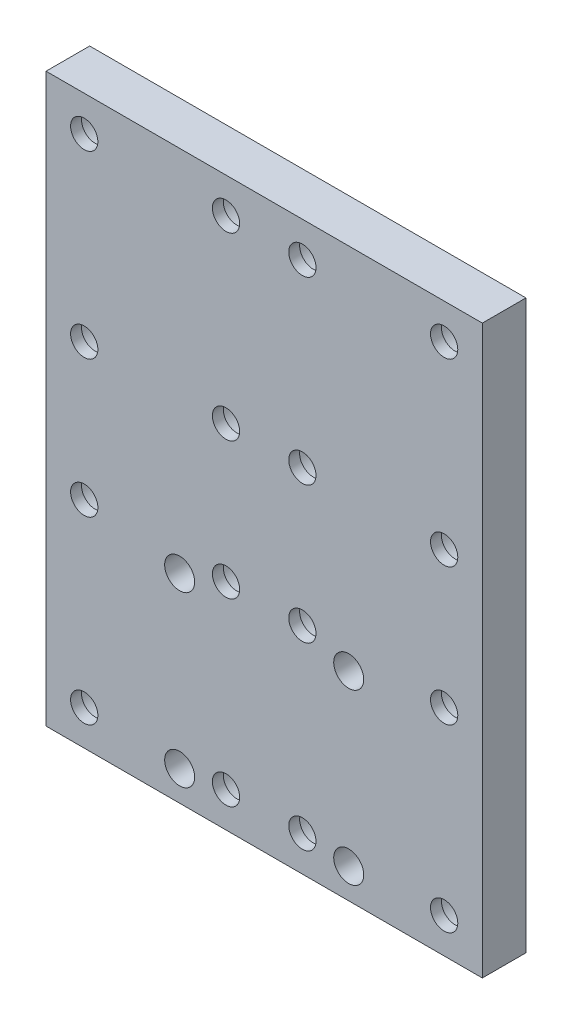
SolidWorks part; units mm, degrees
ref_plane "Ön Düzlem" through (0, 0, 0) normal (0, 0, 1) x (1, 0, 0)
ref_plane "Üst Düzlem" through (0, 0, 0) normal (0, 1, 0) x (1, 0, 0)
ref_plane "Sağ Düzlem" through (0, 0, 0) normal (1, 0, 0) x (0, 0, -1)
sketch "Sketch1" plane through (0, 0, 0) normal (0, 0, 1) x (1, 0, 0)
  line L1 (-40, -52) -> (40, -52)
  line L2 (-40, -52) -> (-40, 52)
  line L3 (-40, 52) -> (40, 52)
  line L4 (40, -52) -> (40, 52)
  line L5 (-40, -52) -> (40, 52) construction
  line L6 (-40, 52) -> (40, -52) construction
  point P0 (0, 0)
  dimension "D1" = 80
  dimension "D2" = 104
extrude "Boss-Extrude1" add sketch "Sketch1" along normal blind 8
sketch "Sketch2" plane through (0, 0, 8) normal (0, 0, 1) x (1, 0, 0)
  line L0 (-20, 29.05) -> (20, 29.05) construction
  line L1 (-33, 45.55) -> (-7, 45.55) construction
  line L2 (-33, 45.55) -> (-33, 12.55) construction
  line L3 (-33, 12.55) -> (-7, 12.55) construction
  line L4 (-7, 45.55) -> (-7, 12.55) construction
  line L5 (-33, 45.55) -> (-7, 12.55) construction
  line L6 (-33, 12.55) -> (-7, 45.55) construction
  line L7 (7, 45.55) -> (33, 45.55) construction
  line L8 (7, 45.55) -> (7, 12.55) construction
  line L9 (7, 12.55) -> (33, 12.55) construction
  line L10 (33, 45.55) -> (33, 12.55) construction
  line L11 (7, 45.55) -> (33, 12.55) construction
  line L12 (7, 12.55) -> (33, 45.55) construction
  line L13 (-33, -12.55) -> (-7, -12.55) construction
  line L14 (-33, -12.55) -> (-33, -45.55) construction
  line L15 (-33, -45.55) -> (-7, -45.55) construction
  line L16 (-7, -12.55) -> (-7, -45.55) construction
  line L17 (-33, -12.55) -> (-7, -45.55) construction
  line L18 (-33, -45.55) -> (-7, -12.55) construction
  line L19 (7, -12.55) -> (33, -12.55) construction
  line L20 (7, -12.55) -> (7, -45.55) construction
  line L21 (7, -45.55) -> (33, -45.55) construction
  line L22 (33, -12.55) -> (33, -45.55) construction
  line L23 (7, -12.55) -> (33, -45.55) construction
  line L24 (7, -45.55) -> (33, -12.55) construction
  line L25 (-20, 29.05) -> (-20, -29.05) construction
  circle A0 centre (-33, 45.55) radius 2.5
  circle A1 centre (-7, 45.55) radius 2.5
  circle A2 centre (-7, 12.55) radius 2.5
  circle A3 centre (-33, 12.55) radius 2.5
  circle A4 centre (33, 45.55) radius 2.5
  circle A5 centre (7, 45.55) radius 2.5
  circle A6 centre (7, 12.55) radius 2.5
  circle A7 centre (33, 12.55) radius 2.5
  circle A8 centre (33, -12.55) radius 2.5
  circle A9 centre (7, -12.55) radius 2.5
  circle A10 centre (33, -45.55) radius 2.5
  circle A11 centre (7, -45.55) radius 2.5
  circle A12 centre (-7, -45.55) radius 2.5
  circle A13 centre (-7, -12.55) radius 2.5
  circle A14 centre (-33, -12.55) radius 2.5
  circle A15 centre (-33, -45.55) radius 2.5
  point P0 (-20, 29.05)
  point P5 (20, 29.05)
  point P10 (-20, -29.05)
  point P15 (20, -29.05)
  point P36 (0, 29.05)
  point P39 (-20, 0)
  dimension "D3" = 5
  dimension "D1" = 26
  dimension "D2" = 33
  dimension "D4" = 58.1
  dimension "D5" = 14
extrude "Cut-Extrude1" cut sketch "Sketch2" against normal blind 8
sketch "Sketch4" plane through (0, 0, 0) normal (0, 0, -1) x (-1, 0, 0)
  circle A0 centre (-33, 45.55) radius 4.25
  circle A1 centre (-7, 45.55) radius 4.25
  circle A2 centre (-7, 12.55) radius 4.25
  circle A3 centre (-33, 12.55) radius 4.25
  circle A4 centre (-33, -12.55) radius 4.25
  circle A5 centre (-7, -12.55) radius 4.25
  circle A6 centre (-7, -45.55) radius 4.25
  circle A7 centre (-33, -45.55) radius 4.25
  circle A8 centre (7, -45.55) radius 4.25
  circle A9 centre (33, -45.55) radius 4.25
  circle A10 centre (7, -12.55) radius 4.25
  circle A11 centre (33, -12.55) radius 4.25
  circle A12 centre (7, 12.55) radius 4.25
  circle A13 centre (33, 12.55) radius 4.25
  circle A14 centre (7, 45.55) radius 4.25
  circle A15 centre (33, 45.55) radius 4.25
  dimension "D2" = 8.5
extrude "Cut-Extrude3" cut sketch "Sketch4" against normal blind 6
sketch "Sketch5" plane through (0, 0, 0) normal (0, 0, -1) x (-1, 0, 0)
  line L1 (-21, -10) -> (21, -10) construction
  line L2 (-21, -10) -> (-21, -52) construction
  line L3 (-21, -52) -> (21, -52) construction
  line L4 (21, -10) -> (21, -52) construction
  line L5 (-21, -10) -> (21, -52) construction
  line L6 (-21, -52) -> (21, -10) construction
  line L8 (40, -52) -> (-40, -52) construction
  line L10 (-15.5, -46.5) -> (15.5, -46.5) construction
  line L11 (-15.5, -46.5) -> (-15.5, -15.5) construction
  line L12 (-15.5, -15.5) -> (15.5, -15.5) construction
  line L13 (15.5, -46.5) -> (15.5, -15.5) construction
  line L14 (-15.5, -46.5) -> (15.5, -15.5) construction
  line L15 (-15.5, -15.5) -> (15.5, -46.5) construction
  circle A0 centre (15.5, -15.5) radius 1.5
  circle A1 centre (-15.5, -15.5) radius 1.5
  circle A2 centre (-15.5, -46.5) radius 1.5
  circle A3 centre (15.5, -46.5) radius 1.5
  point P0 (0, -31)
  point P9 (0, -31)
  dimension "D5" = 3
  dimension "D1" = 42
  dimension "D2" = 42
  dimension "D3" = 31
  dimension "D4" = 31
extrude "Cut-Extrude4" cut sketch "Sketch5" against normal through all
sketch "Sketch6" plane through (0, 0, 8) normal (0, 0, 1) x (1, 0, 0)
  circle A0 centre (15.5, -15.5) radius 2.75
  circle A1 centre (-15.5, -15.5) radius 2.75
  circle A2 centre (15.5, -46.5) radius 2.75
  circle A3 centre (-15.5, -46.5) radius 2.75
  dimension "D1" = 5.5
extrude "Cut-Extrude5" cut sketch "Sketch6" against normal blind 4
